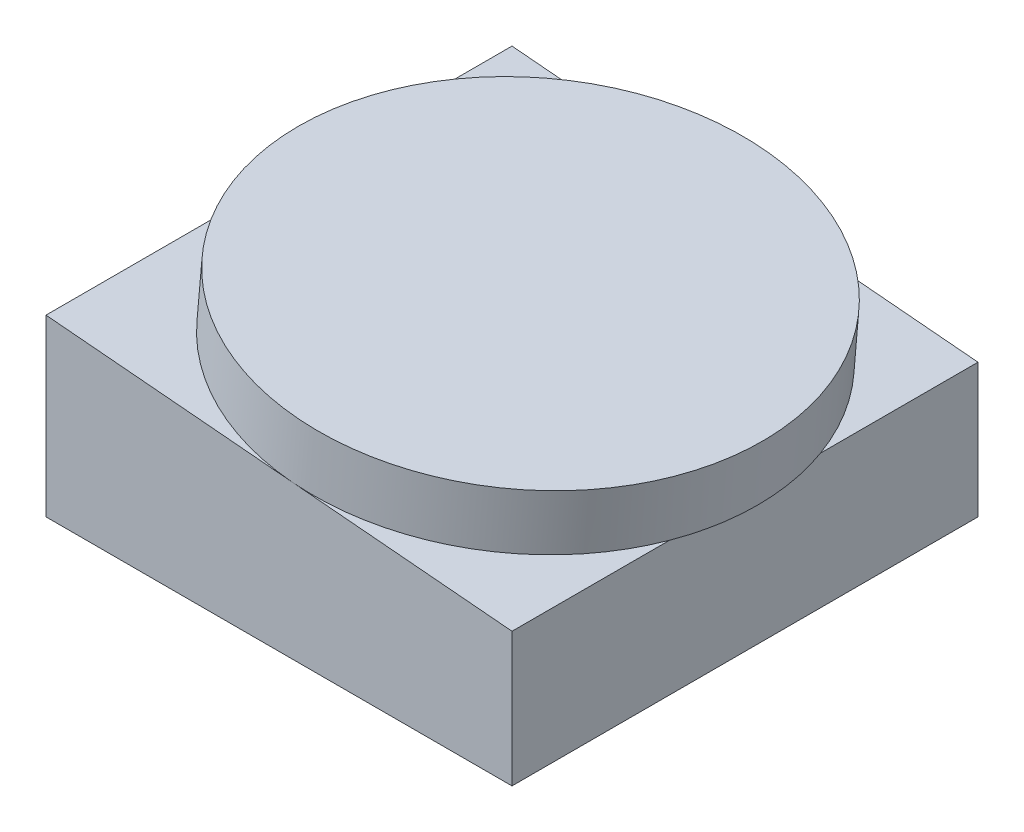
SolidWorks part; units mm, degrees
ref_plane "Front Plane" through (0, 0, 0) normal (0, 0, 1) x (1, 0, 0)
ref_plane "Top Plane" through (0, 0, 0) normal (0, 1, 0) x (1, 0, 0)
ref_plane "Right Plane" through (0, 0, 0) normal (1, 0, 0) x (0, 0, -1)
sketch "Sketch3" plane through (0, 0, 0) normal (0, 1, 0) x (1, 0, 0)
  line L1 (20, -20) -> (-20, -20)
  line L2 (20, -20) -> (20, 20)
  line L3 (20, 20) -> (-20, 20)
  line L4 (-20, -20) -> (-20, 20)
  line L5 (20, -20) -> (-20, 20) construction
  line L6 (20, 20) -> (-20, -20) construction
  point P0 (0, 0)
extrude "Boss-Extrude3" add sketch "Sketch3" along normal blind 15
ref_plane "Plane1" through (1.1504, 13.1496, 0) normal (0.0872, 0.9962, 0) x (0, 0, 1)
sketch "Sketch5" plane through (1.1504, 13.1496, 0) normal (0.0872, 0.9962, 0) x (0, 0, 1)
  line L1 (-26.8089, 24.2265) -> (26.8089, 24.2265)
  line L2 (-26.8089, 24.2265) -> (-26.8089, -24.2265)
  line L3 (-26.8089, -24.2265) -> (26.8089, -24.2265)
  line L4 (26.8089, 24.2265) -> (26.8089, -24.2265)
  line L5 (-26.8089, 24.2265) -> (26.8089, -24.2265) construction
  line L6 (-26.8089, -24.2265) -> (26.8089, 24.2265) construction
  point P0 (0, 0)
extrude "Cut-Extrude1" cut sketch "Sketch5" along normal blind 6 contours L4 L3 L2 L1
sketch "Sketch6" plane through (1.1504, 13.1496, 0) normal (0.0872, 0.9962, 0) x (0.9962, -0.0872, 0)
  circle A0 centre (0, 0) radius 20
extrude "Boss-Extrude4" add sketch "Sketch6" along normal blind 5 contours A0
